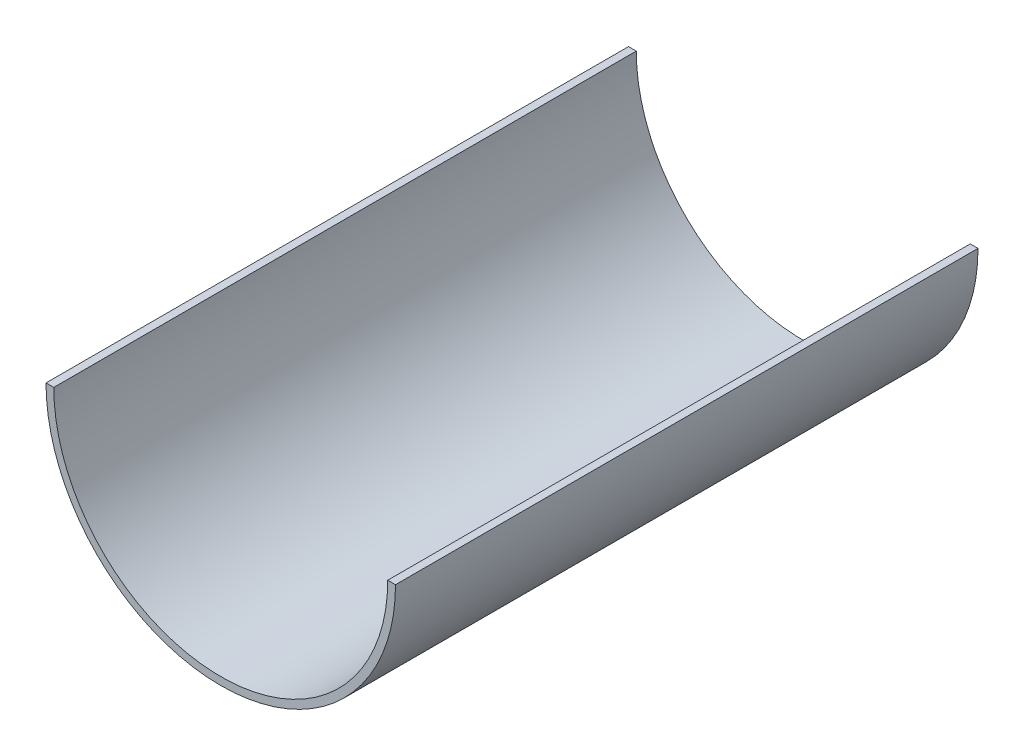
SolidWorks part; units mm, degrees
ref_plane "Front Plane" through (0, 0, 0) normal (0, 0, 1) x (1, 0, 0)
ref_plane "Top Plane" through (0, 0, 0) normal (0, 1, 0) x (1, 0, 0)
ref_plane "Right Plane" through (0, 0, 0) normal (1, 0, 0) x (0, 0, -1)
sketch "Sketch1" plane through (0, 0, 0) normal (0, 0, 1) x (1, 0, 0)
  line L0 (-45, 0) -> (-43, 0)
  line L1 (43, 0) -> (45, 0)
  arc A0 (-43, 0) -> (43, 0) centre (0, 0) ccw
  arc A1 (-45, 0) -> (45, 0) centre (0, 0) ccw
  dimension "D1" = 43
  dimension "D2" = 2
extrude "Boss-Extrude1" add sketch "Sketch1" along normal blind 150
